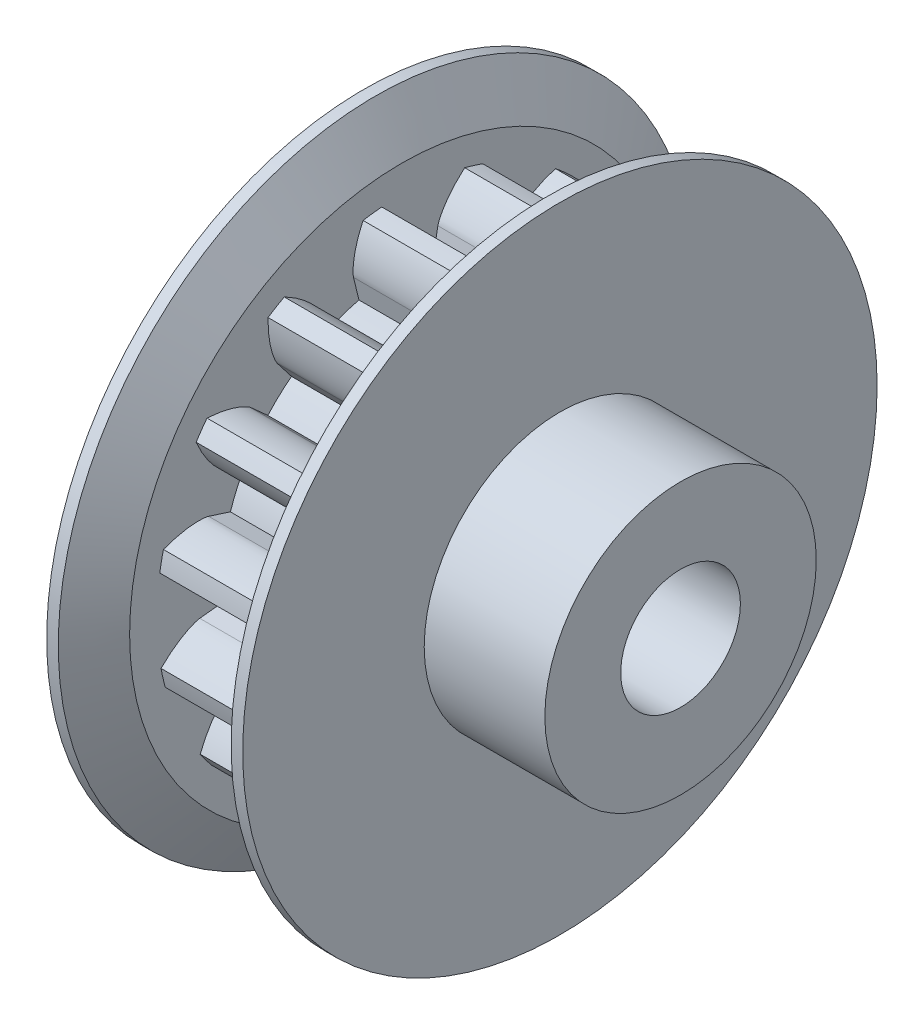
SolidWorks part; units mm, degrees
material "6061-T6 (SS)"
ref_plane "Front Plane" through (0, 0, 0) normal (1, 0, 0) x (0, 1, 0)
ref_plane "Top Plane" through (0, 0, 0) normal (0, 0, 1) x (0, 1, 0)
ref_plane "Right Plane" through (0, 0, 0) normal (0, 1, 0) x (-1, 0, 0)
sketch "Sketch1" plane through (0, 0, 0) normal (1, 0, 0) x (0, 1, 0)
  circle A0 centre (0, 0) radius 8.1169
  circle A1 centre (0, 0) radius 6.7301 construction
  circle A2 centre (0, 0) radius 5.9683 construction
  circle A3 centre (0, 0) radius 7.162 construction
  dimension "D1" = 16.2338
  dimension "D2" = 13.4601
  dimension "D3" = 11.9366
  dimension "D4" = 14.3239
extrude "Boss-Extrude1" add sketch "Sketch1" along normal blind 4
sketch "Sketch3" plane through (4, 0, 0) normal (1, 0, 0) x (0, 1, 0)
  line L0 (0, 0) -> (6.7301, 0) construction
  line L1 (0, 0) -> (7.1612, 0.1067) construction
  line L2 (0, 0) -> (7.1331, -0.6424) construction
  line L3 (7.1331, -0.6424) -> (6.7029, -0.6036)
  line L4 (7.1331, -0.6424) -> (9.2994, -0.8375)
  line L5 (9.2994, 2.0269) -> (9.2994, -0.8375)
  line L6 (6.7301, 0) -> (5.9683, 0)
  line L7 (6.7029, -0.6036) -> (5.9443, -0.5353)
  circle A0 centre (0, 0) radius 7.162 construction
  circle A1 centre (0, 0) radius 6.7301 construction
  circle A2 centre (0, 0) radius 5.9683 construction
  arc A3 (5.9683, 0) -> (5.9443, -0.5353) centre (0, 0) cw
  spline S0 degree 4 poles (6.7301, 0) (6.735, 0.0001) (6.749, 0.0007) (6.7753, 0.0032) (6.818, 0.009) (6.8722, 0.0191) (6.9416, 0.0352) (7.0226, 0.0581) (7.1107, 0.0872) (7.2054, 0.1232) (7.2986, 0.1628) (7.3903, 0.2059) (7.4806, 0.2518) (7.5884, 0.3111) (7.7155, 0.3871) (7.8606, 0.483) (8.0209, 0.6) (8.1793, 0.7277) (8.3309, 0.8602) (8.4788, 1.0018) (8.6182, 1.1441) (8.7571, 1.2994) (8.8824, 1.4465) (9.0159, 1.619) (9.1217, 1.7606) (9.2537, 1.9552) (9.3294, 2.0725) (9.4152, 2.2124) (9.4518, 2.2758) (9.4745, 2.3148) knots 0 0 0 0 0 0.005377 0.015084 0.028532 0.04661 0.064855 0.092111 0.119476 0.146842 0.174209 0.201575 0.228941 0.256307 0.307035 0.361767 0.4165 0.471232 0.525964 0.580697 0.635429 0.690161 0.744894 0.799626 0.854358 0.909091 0.954545 1 1 1 1 1 construction
  spline S1 degree 4 poles (6.7301, 0) (6.735, 0.0001) (6.749, 0.0007) (6.7753, 0.0032) (6.818, 0.009) (6.8722, 0.0191) (6.9416, 0.0352) (7.0226, 0.0581) (7.1107, 0.0872) (7.2054, 0.1232) (7.2986, 0.1628) (7.3903, 0.2059) (7.4806, 0.2518) (7.5884, 0.3111) (7.7155, 0.3871) (7.8606, 0.483) (8.0209, 0.6) (8.1793, 0.7277) (8.3309, 0.8602) (8.4788, 1.0018) (8.6182, 1.1441) (8.7571, 1.2994) (8.8824, 1.4465) (9.0159, 1.619) (9.1217, 1.7606) (9.2251, 1.9131) (9.2745, 1.9881) (9.2994, 2.0269) knots 0 0 0 0 0 0.005377 0.015084 0.028532 0.04661 0.064855 0.092111 0.119476 0.146842 0.174209 0.201575 0.228941 0.256307 0.307035 0.361767 0.4165 0.471232 0.525964 0.580697 0.635429 0.690161 0.744894 0.799626 0.854358 0.909091 0.909091 0.909091 0.909091 0.909091
  dimension "D1" = 6
extrude "Cut-Extrude1" cut sketch "Sketch3" against normal through all
mirror "Mirror1" about plane through (0, 7.1331, -0.6424) normal (0, -0.0897, -0.996) of "Cut-Extrude1"
pattern_circular "CirPattern6" count 15 over 360 about axis through (4, 0, 0) along (-1, 0, 0) of "Cut-Extrude1", "Mirror1"
sketch "Sketch4" plane through (0, 0, 0) normal (0, 1, 0) x (-1, 0, 0)
  line L0 (-9.291, 0) -> (5.5255, 0) construction
  line L1 (-4, 0) -> (-4, 9.0184)
  line L2 (-4, 9.0184) -> (-4.866, 10.5184)
  line L3 (-4.866, 10.5184) -> (-5.25, 10.5184)
  line L4 (-5.25, 10.5184) -> (-5.25, 0)
  line L5 (-5.25, 0) -> (-4, 0)
  line L6 (0, 0) -> (1.25, 0)
  line L7 (1.25, 0) -> (1.25, 10.5184)
  line L8 (1.25, 10.5184) -> (0.866, 10.5184)
  line L9 (0.866, 10.5184) -> (0, 9.0184)
  line L10 (0, 9.0184) -> (0, 0)
  line L11 (-4, 8.0184) -> (0, 8.0184) construction
  dimension "D1" = 150
  dimension "D2" = 150
  dimension "D3" = 1
  dimension "D4" = 1.25
  dimension "D5" = 1.5
revolve "Revolve1" add sketch "Sketch4" angle 360 about L0
sketch "Sketch5" plane through (5.25, 0, 0) normal (1, 0, 0) x (0, 1, 0)
  circle A0 centre (0, 0) radius 4.5
  dimension "D1" = 9
extrude "Boss-Extrude2" add sketch "Sketch5" along normal blind 4
sketch "Sketch6" plane through (9.25, 0, 0) normal (1, 0, 0) x (0, 1, 0)
  circle A0 centre (0, 0) radius 1.9844
  dimension "D1" = 3.9688
extrude "Cut-Extrude2" cut sketch "Sketch6" against normal through all
equation "\"DiametralPitch\"= pi / \"Pitch\""
equation "\"NumberTeeth\"= 15"
equation "\"PressureAngle\"= 20"
equation "\"PitchDiameter\"= \"NumberTeeth\" / \"DiametralPitch\""
equation "\"BaseDiameter\"= \"PitchDiameter\" * cos ( \"PressureAngle\" )"
equation "\"Addendum\"= 1 / \"DiametralPitch\""
equation "\"Dedendum\"= 1.25 / \"DiametralPitch\""
equation "\"AddendumDiameter\"= \"PitchDiameter\" + \"Addendum\" + \"Addendum\""
equation "\"DedendumDiameter\"= \"PitchDiameter\" - \"Dedendum\" - \"Dedendum\""
equation "\"ToothSpacing\"= 360 / ( 4 * \"NumberTeeth\" )"
equation "\"D1@Sketch1\"=\"AddendumDiameter\""
equation "\"D2@Sketch1\"=\"BaseDiameter\""
equation "\"D3@Sketch1\"=\"DedendumDiameter\""
equation "\"D4@Sketch1\"=\"PitchDiameter\""
equation "\"D1@Sketch3\"=\"ToothSpacing\""
equation "\"D1@CirPattern6\"=\"NumberTeeth\""
equation "\"Pitch\"= 3"
equation "\"D1@Sketch6\"=5/32*25.4"
